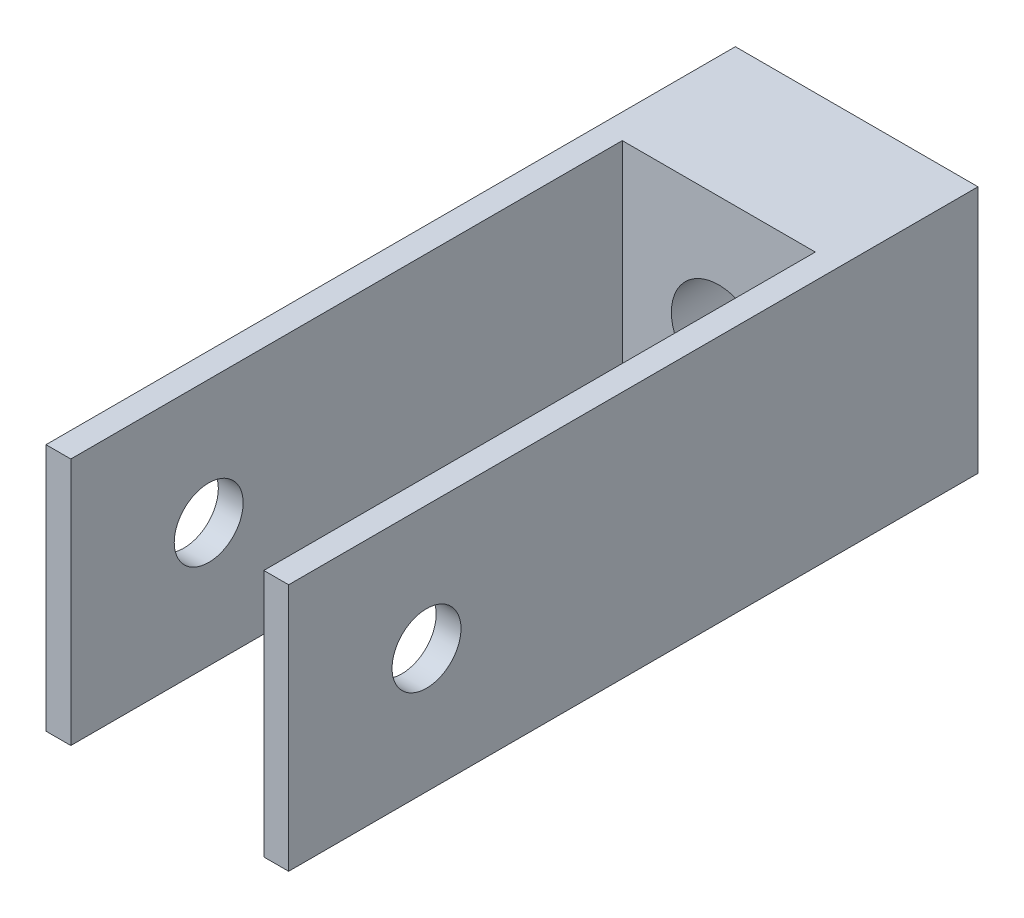
SolidWorks part; units mm, degrees
ref_plane "Front Plane" through (0, 0, 0) normal (0, 0, 1) x (1, 0, 0)
ref_plane "Top Plane" through (0, 0, 0) normal (0, 1, 0) x (1, 0, 0)
ref_plane "Right Plane" through (0, 0, 0) normal (1, 0, 0) x (0, 0, -1)
sketch "Sketch1" plane through (0, 0, 0) normal (0, 1, 0) x (1, 0, 0)
  line L0 (-11.176, -25.4) -> (-8.89, -25.4)
  line L1 (-11.176, 38.1) -> (11.176, 38.1)
  line L2 (-11.176, 38.1) -> (-11.176, -25.4)
  line L4 (11.176, 38.1) -> (11.176, -25.4)
  line L5 (-8.89, 25.4) -> (8.89, 25.4)
  line L6 (-8.89, 25.4) -> (-8.89, -25.4)
  line L8 (8.89, 25.4) -> (8.89, -25.4)
  line L9 (8.89, -25.4) -> (11.176, -25.4)
  point P8 (0, 25.4)
  point P11 (8.89, 0)
  dimension "D1" = 2.286
  dimension "D2" = 17.78
  dimension "D3" = 50.8
  dimension "D4" = 12.7
extrude "Boss-Extrude1" add sketch "Sketch1" along normal blind 22.86
sketch "Sketch2" plane through (11.176, 0, 0) normal (1, 0, 0) x (0, 0, -1)
  line L0 (-25.4, 22.86) -> (-25.4, 0) construction
  circle A0 centre (-12.7, 11.43) radius 3.175
  point P5 (-25.4, 11.43)
  dimension "D2" = 6.35
  dimension "D1" = 12.7
extrude "Cut-Extrude1" cut sketch "Sketch2" against normal through all
sketch "Sketch3" plane through (0, 0, -38.1) normal (0, 0, -1) x (-1, 0, 0)
  line L0 (-11.176, 22.86) -> (-11.176, 0) construction
  circle A0 centre (0, 11.43) radius 4.3656
  point P9 (-11.176, 11.43)
  dimension "D1" = 8.7312
extrude "Cut-Extrude2" cut sketch "Sketch3" against normal blind 23.622
